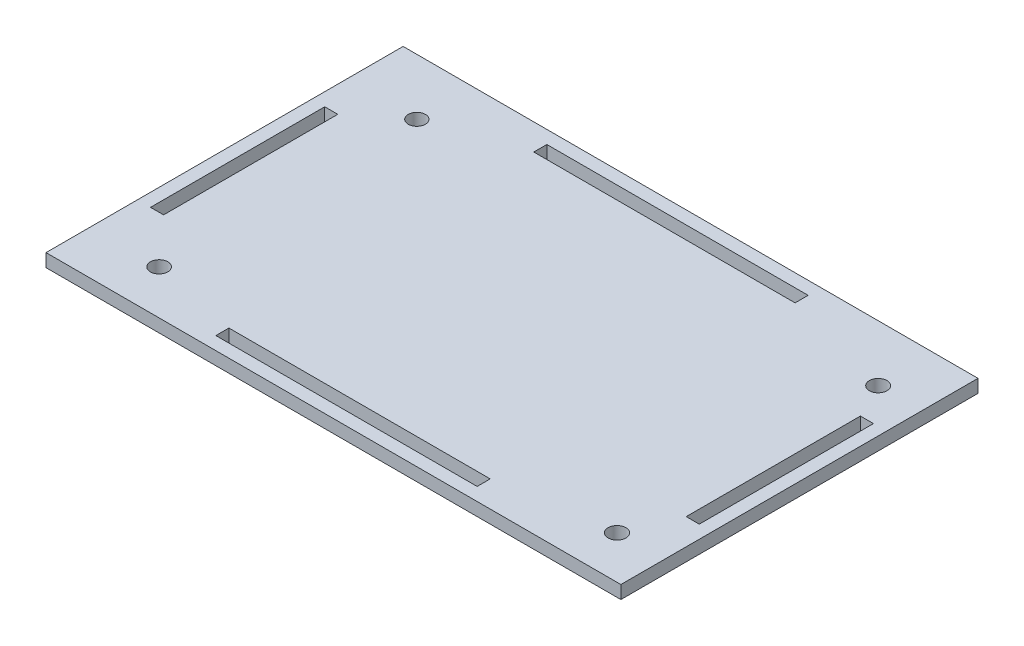
SolidWorks part; units mm, degrees
ref_plane "Front Plane" through (0, 0, 0) normal (0, 0, 1) x (1, 0, 0)
ref_plane "Top Plane" through (0, 0, 0) normal (0, 1, 0) x (1, 0, 0)
ref_plane "Right Plane" through (0, 0, 0) normal (1, 0, 0) x (0, 0, -1)
sketch "Sketch2" plane through (0, 0, 0) normal (0, 1, 0) x (1, 0, 0)
  line L0 (0, 70) -> (0, 0) construction
  line L1 (0, 0) -> (-120, 0) construction
  line L2 (0, 0) -> (0, 70) construction
  line L3 (0, 70) -> (-120, 70) construction
  line L4 (-120, 0) -> (-120, 70) construction
  line L9 (0, 35) -> (1.5, 35) construction
  line L10 (-120, 70) -> (-120, 0) construction
  line L11 (3, 55) -> (0, 55)
  line L12 (3, 55) -> (3, 15)
  line L13 (3, 15) -> (0, 15)
  line L14 (0, 55) -> (0, 15)
  line L15 (3, 55) -> (0, 15) construction
  line L16 (3, 15) -> (0, 55) construction
  line L17 (-120, 35) -> (-121.5, 35) construction
  line L18 (-60, 70) -> (-60, 71.5) construction
  line L19 (-123, 55) -> (-120, 55)
  line L20 (-123, 55) -> (-123, 15)
  line L21 (-123, 15) -> (-120, 15)
  line L22 (-120, 55) -> (-120, 15)
  line L23 (-123, 55) -> (-120, 15) construction
  line L24 (-123, 15) -> (-120, 55) construction
  line L25 (-60, 0) -> (-60, -1.5) construction
  line L26 (-30, 73) -> (-90, 73)
  line L27 (-30, 73) -> (-30, 70)
  line L28 (-30, 70) -> (-90, 70)
  line L29 (-90, 73) -> (-90, 70)
  line L30 (-30, 73) -> (-90, 70) construction
  line L31 (-30, 70) -> (-90, 73) construction
  line L32 (0, 0) -> (6, 0) construction
  line L33 (-30, -3) -> (-90, -3)
  line L34 (-30, -3) -> (-30, 0)
  line L35 (-30, 0) -> (-90, 0)
  line L36 (-90, -3) -> (-90, 0)
  line L37 (-30, -3) -> (-90, 0) construction
  line L38 (-30, 0) -> (-90, -3) construction
  line L39 (6, 0) -> (6, -6) construction
  line L40 (-120, 70) -> (-120, 76) construction
  line L41 (-120, 76) -> (-126, 76) construction
  line L43 (6, -6) -> (-126, -6)
  line L44 (6, -6) -> (6, 76)
  line L45 (6, 76) -> (-126, 76)
  line L46 (-126, -6) -> (-126, 76)
  circle A0 centre (-110.1808, 4.1548) radius 2.0065
  circle A1 centre (-109.9268, 63.0805) radius 1.9738
  circle A2 centre (-4.7202, 3.8378) radius 2.0487
  circle A3 centre (-4.0043, 63.0805) radius 2.0244
  point P45 (-4.0043, 63.0805)
extrude "Boss-Extrude1" add sketch "Sketch2" along normal blind 3
